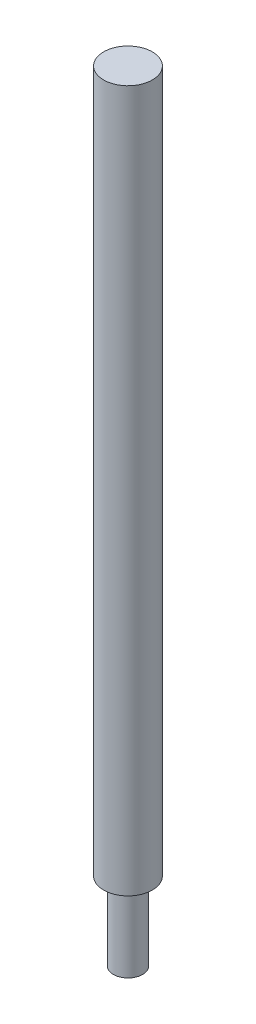
SolidWorks part; units mm, degrees
ref_plane "Front Plane" through (0, 0, 0) normal (0, 0, 1) x (1, 0, 0)
ref_plane "Top Plane" through (0, 0, 0) normal (0, 1, 0) x (1, 0, 0)
ref_plane "Right Plane" through (0, 0, 0) normal (1, 0, 0) x (0, 0, -1)
sketch "Sketch1" plane through (0, 0, 0) normal (0, 1, 0) x (1, 0, 0)
  circle A0 centre (0, 0) radius 1.5
  dimension "D1" = 3
extrude "Boss-Extrude1" add sketch "Sketch1" along normal blind 8
sketch "Sketch2" plane through (0, 8, 0) normal (0, 1, 0) x (1, 0, 0)
  circle A0 centre (0, 0) radius 2.5
  dimension "D1" = 5
extrude "Boss-Extrude2" add sketch "Sketch2" along normal blind 72
